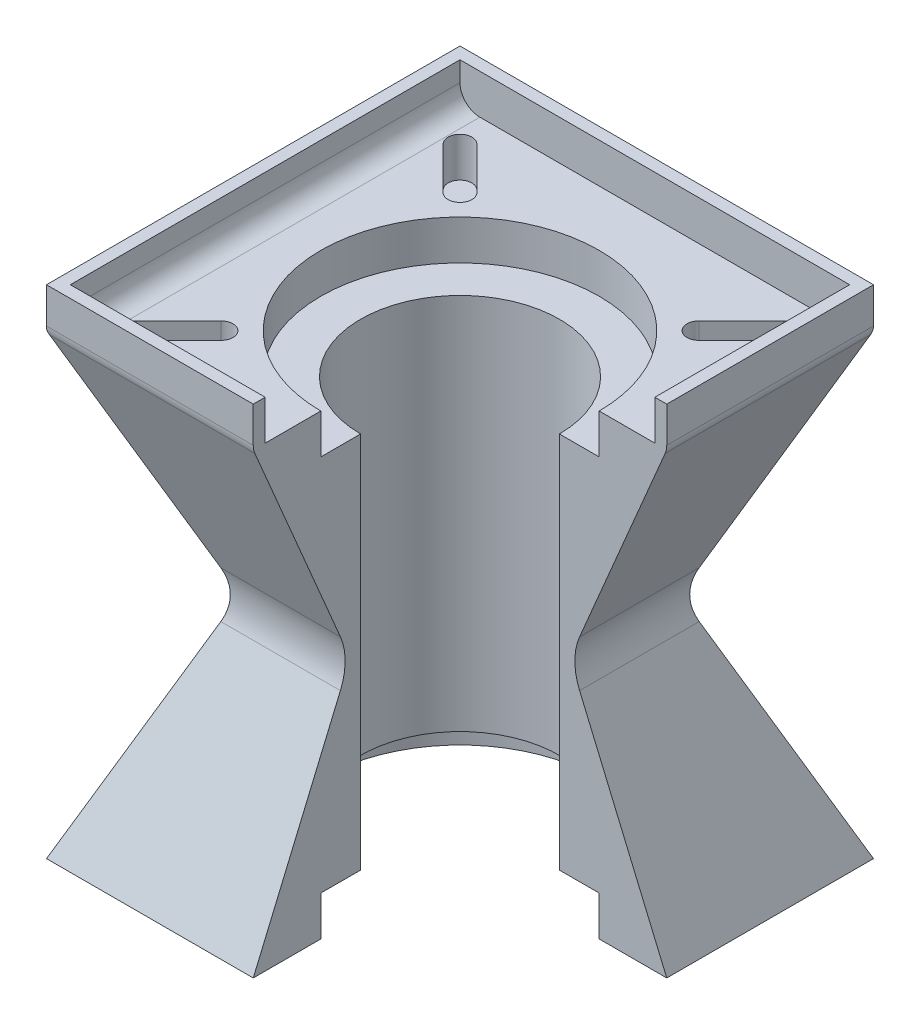
SolidWorks part; units mm, degrees
material "Cast Stainless Steel"
ref_plane "Front Plane" through (0, 0, 0) normal (0, 0, 1) x (1, 0, 0)
ref_plane "Top Plane" through (0, 0, 0) normal (0, 1, 0) x (1, 0, 0)
ref_plane "Right Plane" through (0, 0, 0) normal (1, 0, 0) x (0, 0, -1)
sketch "Sketch1" plane through (0, 0, 0) normal (0, 1, 0) x (1, 0, 0)
  line L1 (0, 0) -> (104, 0)
  line L2 (0, 0) -> (0, 104)
  line L3 (0, 104) -> (104, 104)
  line L4 (104, 0) -> (104, 104)
  dimension "D1" = 104
  dimension "D2" = 104
extrude "Boss-Extrude1" add sketch "Sketch1" along normal mid plane 115
sketch "Sketch2" plane through (0, 0, 0) normal (0, 0, 1) x (1, 0, 0)
  line L0 (0, -57.5) -> (24.4073, 0)
  line L1 (24.4073, 0) -> (0, 57.5)
  line L2 (0, 57.5) -> (0, -57.5)
  line L3 (104, 57.5) -> (79.5927, 0)
  line L4 (79.5927, 0) -> (104, -57.5)
  line L5 (104, -57.5) -> (104, 57.5)
  dimension "D1" = 23
extrude "Cut-Extrude1" cut sketch "Sketch2" against normal blind 104
ref_plane "Plane1" through (104, 0, 0) normal (-1, 0, 0) x (0, 0, 1)
sketch "Sketch3" plane through (104, 0, 0) normal (-1, 0, 0) x (0, 0, 1)
  line L0 (-104, 57.5) -> (-79.5927, 0)
  line L1 (-104, 0) -> (0, 0) construction
  line L2 (-79.5927, 0) -> (-104, -57.5)
  line L3 (-104, -57.5) -> (-104, 57.5)
  line L4 (0, 57.5) -> (-24.4073, 0)
  line L5 (-24.4073, 0) -> (0, -57.5)
  line L6 (0, -57.5) -> (0, 57.5)
  dimension "D1" = 23
extrude "Cut-Extrude2" cut sketch "Sketch3" along normal blind 104
sketch "Sketch4" plane through (0, 57.5, 0) normal (0, 1, 0) x (1, 0, 0)
  circle A0 centre (52, 52) radius 25
  dimension "D1" = 50
  dimension "D2" = 52
  dimension "D3" = 52
extrude "Cut-Extrude3" cut sketch "Sketch4" against normal blind 115
sketch "Sketch5" plane through (0, 57.5, 0) normal (0, 1, 0) x (1, 0, 0)
  circle A0 centre (52, 52) radius 25 construction
  circle A1 centre (52, 52) radius 25
  circle A2 centre (52, 52) radius 35
  dimension "D1" = 70
extrude "Cut-Extrude4" cut sketch "Sketch5" against normal blind 10
sketch "Sketch6" plane through (0, -57.5, 0) normal (0, -1, 0) x (1, 0, 0)
  line L4 (0, 0) -> (0, -104)
  line L5 (0, -104) -> (104, -104)
  line L6 (104, -104) -> (104, 0)
  line L7 (104, 0) -> (0, 0)
  line L8 (0, 0) -> (0, -104)
  line L9 (0, -104) -> (104, -104)
  line L10 (104, -104) -> (104, 0)
  line L11 (104, 0) -> (0, 0)
  circle A0 centre (52, -52) radius 25 construction
  circle A1 centre (52, -52) radius 25
  circle A2 centre (52, -52) radius 35
  dimension "D2" = 70
  dimension "D1" = 0
extrude "Cut-Extrude5" cut sketch "Sketch6" against normal blind 10 contours A2
sketch "Sketch7" plane through (0, 57.5, 0) normal (0, 1, 0) x (1, 0, 0)
  line L0 (52, 77) -> (52, 27) construction
  line L1 (27, 52) -> (77, 52) construction
  line L3 (104, 0) -> (52, 0)
  line L4 (104, 0) -> (104, 52)
  line L5 (104, 52) -> (52, 52)
  line L6 (52, 0) -> (52, 52)
  circle A0 centre (52, 52) radius 25 construction
extrude "Cut-Extrude6" cut sketch "Sketch7" against normal blind 115
fillet "Fillet1" radius 15 4 edges at (24.4073, 0, -52) (52, 0, -79.5927) (79.5927, 0, -65.7963) (38.2037, 0, -24.4073)
sketch "Sketch8" plane through (0, 57.5, 0) normal (0, 1, 0) x (1, 0, 0)
  line L0 (101, 52) -> (101, 101)
  line L1 (101, 101) -> (3, 101)
  line L2 (3, 101) -> (3, 3)
  line L3 (3, 3) -> (52, 3)
  line L4 (101, 52) -> (104, 52)
  line L5 (52, 3) -> (52, 0)
  line L6 (0, 0) -> (52, 0)
  line L7 (52, 0) -> (52, 17)
  line L8 (87, 52) -> (104, 52)
  line L9 (104, 52) -> (104, 104)
  line L10 (104, 104) -> (0, 104)
  line L11 (0, 104) -> (0, 0)
  line L12 (0, 0) -> (52, 0)
  line L13 (52, 0) -> (52, 17)
  line L14 (87, 52) -> (104, 52)
  line L15 (104, 52) -> (104, 104)
  line L16 (104, 104) -> (0, 104)
  line L17 (0, 104) -> (0, 0)
  arc A1 (87, 52) -> (52, 17) centre (52, 52) ccw
  arc A2 (87, 52) -> (52, 17) centre (52, 52) ccw
  line M8 (0, 0) -> (52, 0)
  line M9 (52, 0) -> (52, 17)
  line M11 (87, 52) -> (104, 52)
  line M12 (104, 52) -> (104, 104)
  line M13 (104, 104) -> (0, 104)
  line M14 (0, 104) -> (0, 0)
  dimension "D1" = 0
  dimension "D2" = 3
extrude "Boss-Extrude2" add sketch "Sketch8" along normal blind 10 contours L3 L2 L1 L0 M11 M12 M13 M14 M8 M9
sketch "Sketch9" plane through (0, 57.5, 0) normal (0, 1, 0) x (1, 0, 0)
  line L0 (0, 0) -> (101, 101) construction
  line L1 (3, 101) -> (52, 52) construction
  line L2 (11.3414, 92.6586) -> (21.948, 82.052) construction
  line L5 (13.4627, 94.78) -> (24.0693, 84.1734)
  line L8 (9.22, 90.5373) -> (19.8266, 79.9307)
  line L11 (92.6586, 92.6586) -> (82.052, 82.052) construction
  line L12 (94.78, 90.5373) -> (84.1734, 79.9307)
  line L13 (90.5373, 94.78) -> (79.9307, 84.1734)
  line L14 (21.948, 21.948) -> (11.3414, 11.3414) construction
  line L15 (24.0693, 19.8266) -> (13.4627, 9.22)
  line L16 (19.8266, 24.0693) -> (9.22, 13.4627)
  arc A6 (13.4627, 94.78) -> (9.22, 90.5373) centre (11.3414, 92.6586) ccw
  arc A7 (19.8266, 79.9307) -> (24.0693, 84.1734) centre (21.948, 82.052) ccw
  arc A8 (94.78, 90.5373) -> (90.5373, 94.78) centre (92.6586, 92.6586) ccw
  arc A9 (79.9307, 84.1734) -> (84.1734, 79.9307) centre (82.052, 82.052) ccw
  arc A10 (24.0693, 19.8266) -> (19.8266, 24.0693) centre (21.948, 21.948) ccw
  arc A11 (9.22, 13.4627) -> (13.4627, 9.22) centre (11.3414, 11.3414) ccw
  point P8 (16.6447, 87.3553)
  point P13 (87.3553, 87.3553)
  point P20 (16.6447, 16.6447)
  dimension "D2" = 3
  dimension "D1" = 15
  dimension "D3" = 50
  dimension "D4" = 50
  dimension "D5" = 50
extrude "Cut-Extrude7" cut sketch "Sketch9" against normal blind 10
fillet "Fillet2" radius 5 4 edges at (104, 57.5, -78) (52, 57.5, -104) (3, 57.5, -52) (26, 57.5, 0)
equation "\"A\"= 115mm"
equation "\"B\"= 104mm"
equation "\"C\"= 23mm"
